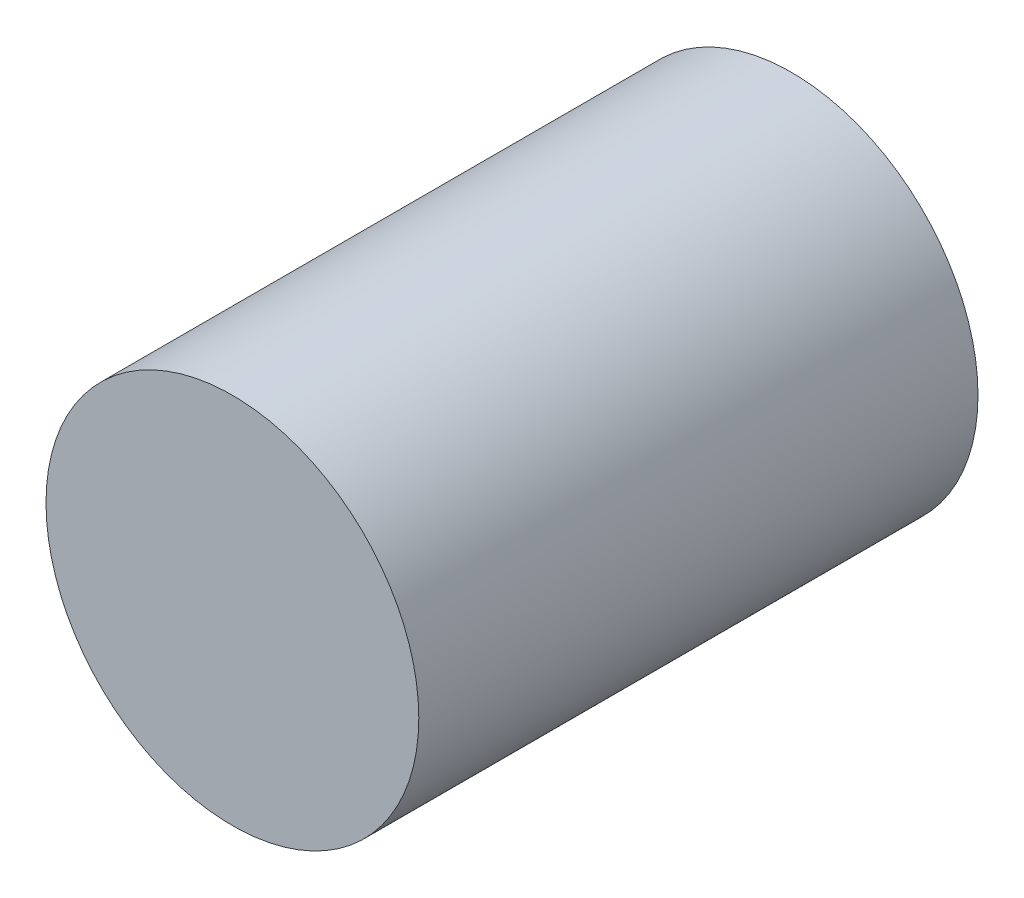
SolidWorks part; units mm, degrees
material "Stainless Steel (ferritic)"
ref_plane "Front Plane" through (0, 0, 0) normal (0, 0, 1) x (1, 0, 0)
ref_plane "Top Plane" through (0, 0, 0) normal (0, 1, 0) x (1, 0, 0)
ref_plane "Right Plane" through (0, 0, 0) normal (1, 0, 0) x (0, 0, -1)
sketch "Sketch1" plane through (0, 0, 0) normal (0, 0, 1) x (1, 0, 0)
  circle A0 centre (0, 0) radius 6.35
  dimension "D1" = 12.7
extrude "Boss-Extrude1" add sketch "Sketch1" along normal blind 19.05
